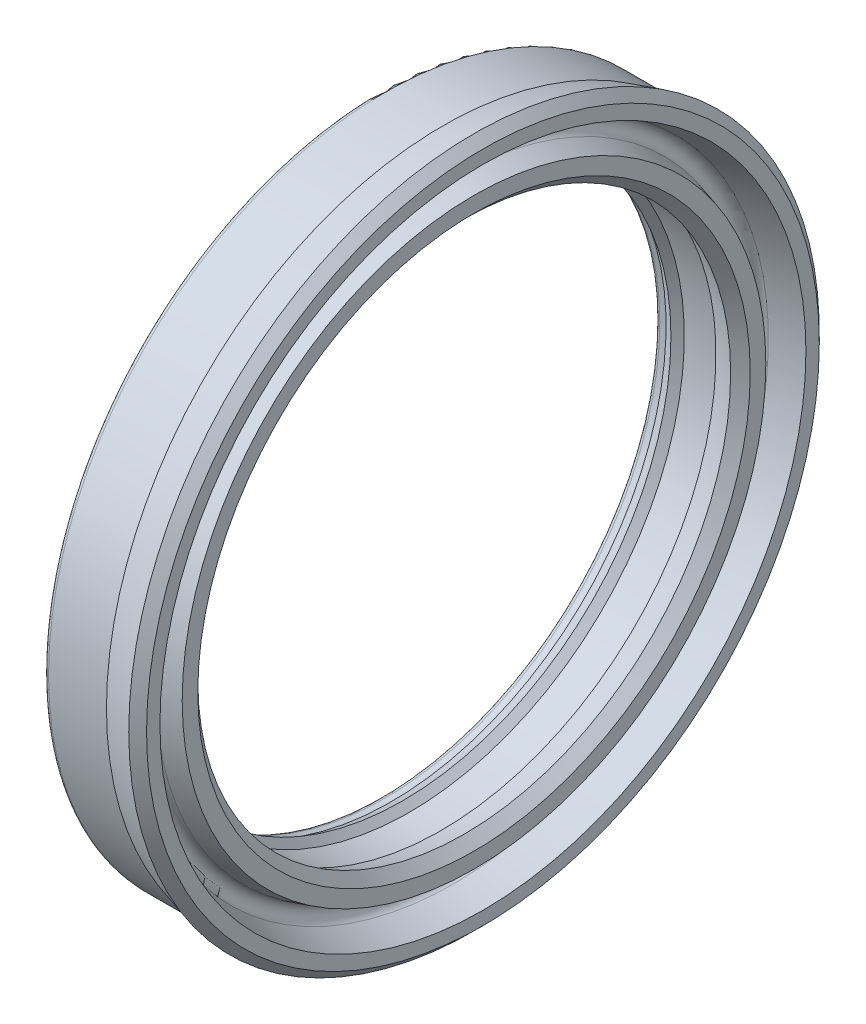
SolidWorks part; units mm, degrees
material "TPU-95A"
ref_plane "Front Plane" through (0, 0, 0) normal (0, 0, 1) x (1, 0, 0)
ref_plane "Top Plane" through (0, 0, 0) normal (0, 1, 0) x (1, 0, 0)
ref_plane "Right Plane" through (0, 0, 0) normal (1, 0, 0) x (0, 0, -1)
sketch "Sketch1" plane through (0, 0, 0) normal (0, 0, 1) x (1, 0, 0)
  line L0 (0, 0) -> (70.2538, 0) construction
  line L1 (0, 30.85) -> (0, 37.75)
  line L2 (0, 37.75) -> (7, 37.75)
  line L3 (7, 37.75) -> (10.5, 38.75)
  line L4 (11.5, 37.75) -> (11.5, 36.25)
  line L5 (11.5, 36.25) -> (8.2245, 35.3113)
  line L6 (1.201, 30.85) -> (2.5, 30.1)
  line L7 (8.2298, 33.3872) -> (10.5, 32.75)
  line L8 (10.5, 32.75) -> (10.5, 31)
  line L9 (0, 30.85) -> (1.201, 30.85)
  line L10 (6.8, 30.85) -> (9.4, 29.9)
  line L11 (2.5, 30.1) -> (3.25, 30.85)
  line L12 (3.25, 30.85) -> (6.8, 30.85)
  line L13 (9.4, 29.9) -> (10.5, 31)
  line L14 (10.5, 38.75) -> (11.5, 37.75)
  arc A0 (8.2245, 35.3113) -> (8.2298, 33.3872) centre (8.5, 34.35) ccw
  dimension "D8" = 1
  dimension "D9" = 3.5
  dimension "D10" = 4
  dimension "D1" = 61.7
  dimension "D2" = 62
  dimension "D3" = 65.5
  dimension "D4" = 6.8
  dimension "D5" = 75.5
  dimension "D6" = 1
  dimension "D7" = 77.5
  dimension "D11" = 60.2
  dimension "D12" = 30
  dimension "D13" = 45
  dimension "D14" = 2.5
  dimension "D15" = 59.8
  dimension "D16" = 45
  dimension "D17" = 11.5
  dimension "D18" = 72.5
  dimension "D19" = 7
  dimension "D20" = 45
  dimension "D21" = 1
revolve "Revolve1" add sketch "Sketch1" angle 360 about L0
fillet "Fillet1" radius 0.5 2 edges at (0, 0, 30.85) (0, 0, 37.75)
